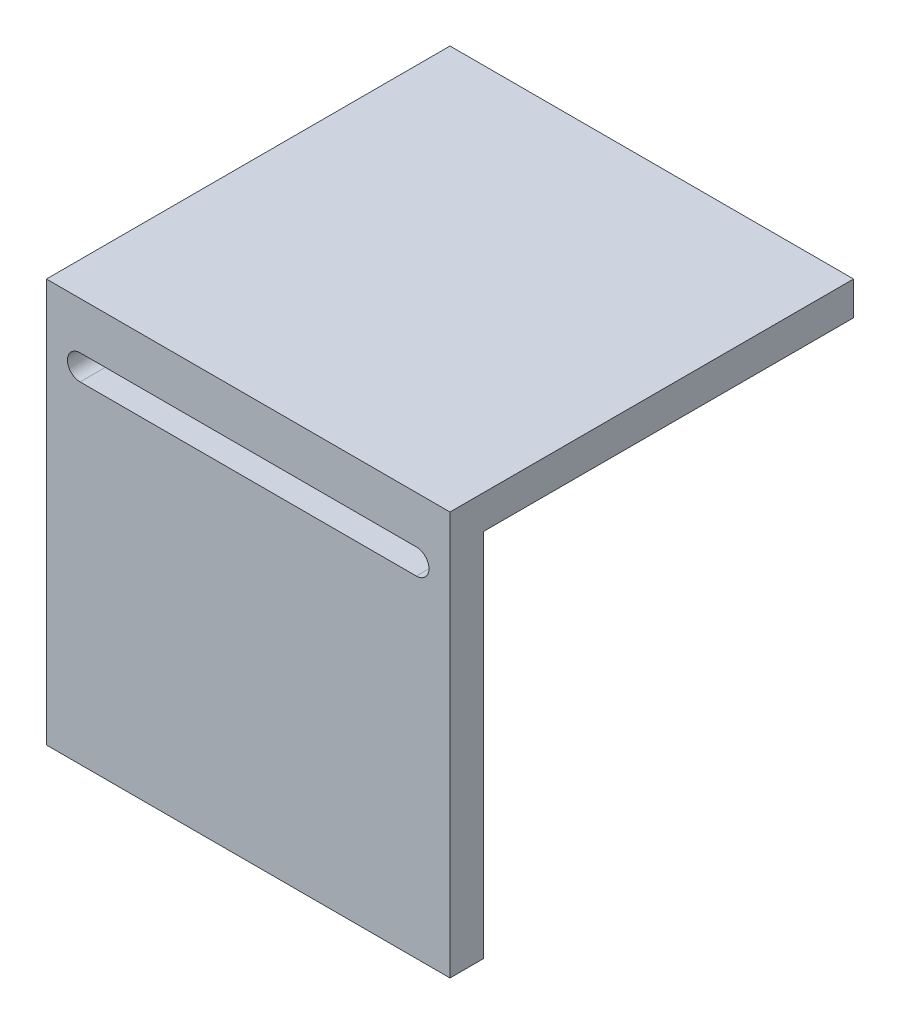
SolidWorks part; units mm, degrees
ref_plane "Front Plane" through (0, 0, 0) normal (0, 0, 1) x (1, 0, 0)
ref_plane "Top Plane" through (0, 0, 0) normal (0, 1, 0) x (1, 0, 0)
ref_plane "Right Plane" through (0, 0, 0) normal (1, 0, 0) x (0, 0, -1)
sketch "Sketch1" plane through (0, 0, 0) normal (1, 0, 0) x (0, 0, -1)
  line L0 (-6.35, 76.2) -> (69.85, 76.2)
  line L1 (69.85, 76.2) -> (69.85, 69.85)
  line L2 (69.85, 69.85) -> (0, 69.85)
  line L3 (0, 69.85) -> (0, 0)
  line L4 (0, 0) -> (-6.35, 0)
  line L5 (-6.35, 0) -> (-6.35, 76.2)
  line L6 (0, 38.4175) -> (0, -38.4175) construction
  line L7 (38.4175, 0) -> (-38.4175, 0) construction
  dimension "D1" = 6.35
  dimension "D2" = 6.35
  dimension "D3" = 76.2
  dimension "D4" = 76.2
extrude "Boss-Extrude1" add sketch "Sketch1" along normal blind 76.2
sketch "Sketch7" plane through (0, 0, 0) normal (0, 0, -1) x (-1, 0, 0)
  line L0 (-69.85, 64.9288) -> (-6.35, 64.9287) construction
  line L1 (-69.85, 67.31) -> (-6.35, 67.31)
  line L2 (-69.85, 62.5475) -> (-6.35, 62.5475)
  line L3 (-76.2, 69.85) -> (0, 69.85) construction
  line L4 (0, 0) -> (0, 69.85) construction
  arc A0 (-69.85, 67.31) -> (-69.85, 62.5475) centre (-69.85, 64.9288) ccw
  arc A1 (-6.35, 62.5475) -> (-6.35, 67.31) centre (-6.35, 64.9287) ccw
  point P2 (-38.1, 64.9287)
  dimension "D1" = 4.7625
  dimension "D2" = 2.54
  dimension "D3" = 63.5
  dimension "D4" = 6.35
extrude "Cut-Extrude3" cut sketch "Sketch7" against normal through all
